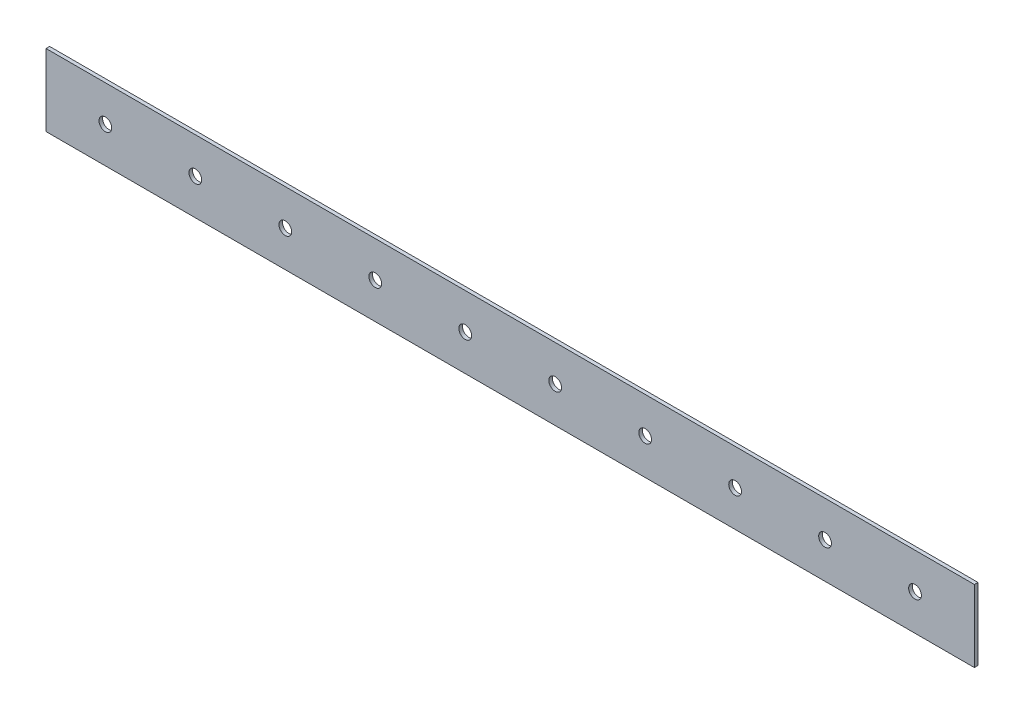
SolidWorks part; units mm, degrees
ref_plane "정면" through (0, 0, 0) normal (0, 0, 1) x (1, 0, 0)
ref_plane "윗면" through (0, 0, 0) normal (0, 1, 0) x (1, 0, 0)
ref_plane "우측면" through (0, 0, 0) normal (1, 0, 0) x (0, 0, -1)
sketch "스케치1" plane through (0, 0, 0) normal (0, 0, 1) x (1, 0, 0)
  line L0 (0, 0) -> (-112.7244, 0) construction
  line L1 (-129, 10) -> (129, 10)
  line L2 (-129, 10) -> (-129, -10)
  line L3 (-129, -10) -> (129, -10)
  line L4 (129, 10) -> (129, -10)
  line L5 (-129, 10) -> (129, -10) construction
  line L6 (-129, -10) -> (129, 10) construction
  line L7 (0, 0) -> (0, 10) construction
  circle A0 centre (-12.5, 0) radius 1.7711
  circle A2 centre (-37.5, 0) radius 1.7711
  circle A3 centre (-62.5, 0) radius 1.7711
  circle A4 centre (-87.5, 0) radius 1.7711
  circle A5 centre (-112.5, 0) radius 1.7711
  circle A6 centre (112.5, 0) radius 1.7711
  circle A7 centre (87.5, 0) radius 1.7711
  circle A8 centre (62.5, 0) radius 1.7711
  circle A9 centre (37.5, 0) radius 1.7711
  circle A10 centre (12.5, 0) radius 1.7711
  point P0 (0, 0)
  dimension "D1" = 258
  dimension "D2" = 20
  dimension "D4" = 12.5
  dimension "D3" = 5
extrude "보스-돌출1" add sketch "스케치1" along normal blind 1
